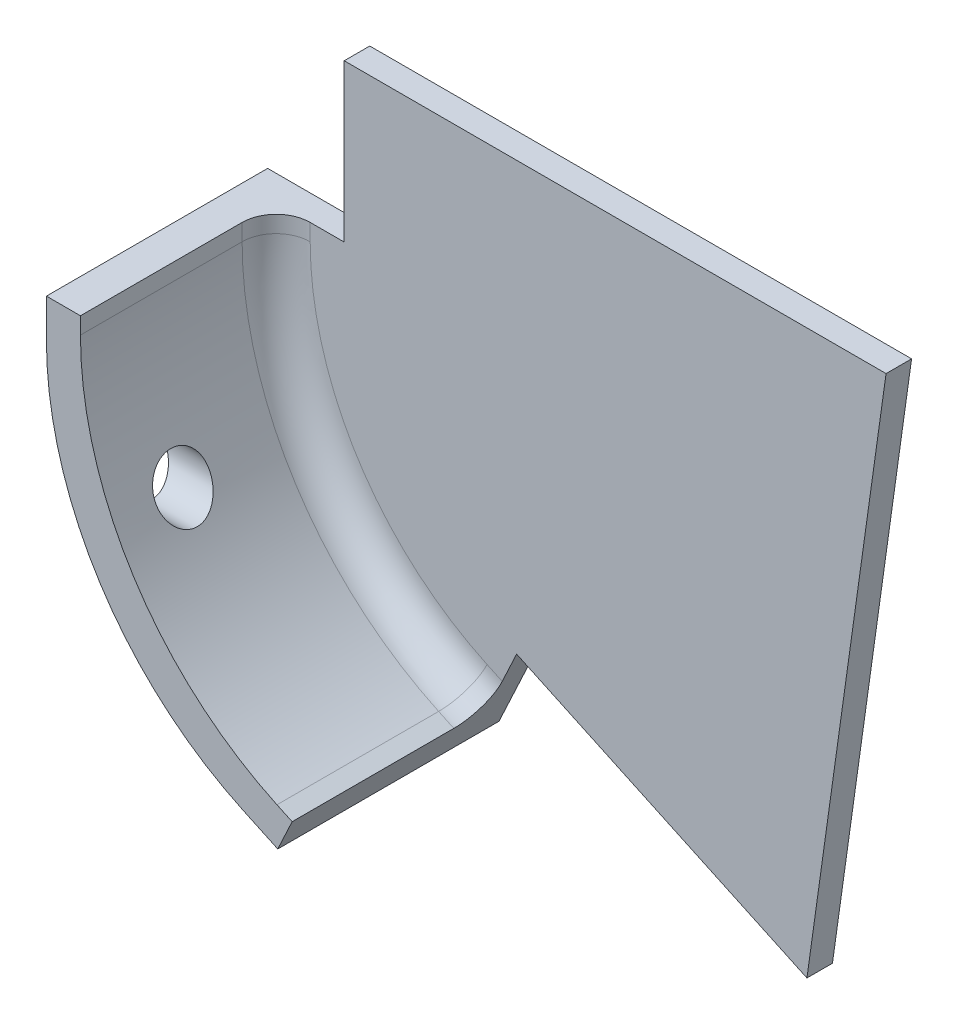
SolidWorks part; units mm, degrees
material "POLYURETHANE (11671)"
ref_plane "Front Plane" through (0, 0, 0) normal (0, 0, 1) x (1, 0, 0)
ref_plane "Top Plane" through (0, 0, 0) normal (0, 1, 0) x (1, 0, 0)
ref_plane "Right Plane" through (0, 0, 0) normal (1, 0, 0) x (0, 0, -1)
sketch "Sketch1" plane through (0, 0, 0) normal (0, 0, 1) x (1, 0, 0)
  line L0 (-4.4818, -31.0063) -> (9.1128, -37.3455)
  line L5 (-18.0764, -4.2621) -> (13.7624, -4.2621)
  line L6 (-18.0764, -4.2621) -> (-18.0764, -9.667)
  line L9 (9.1128, -37.3455) -> (13.7624, -4.2621)
  line L14 (-18.0764, -9.667) -> (-18.0764, -24.667)
  line L15 (-4.4818, -31.0063) -> (-18.0764, -24.667)
  dimension "D4" = 82
  dimension "D3" = 115
extrude "Boss-Extrude1" add sketch "Sketch1" along normal blind 1.5
sketch "Sketch2" plane through (0, 0, 0) normal (0, 0, -1) x (-1, 0, 0)
  line L0 (24.0764, -28.4894) -> (24.0764, -13.4894)
  line L1 (24.0764, -13.4894) -> (17.0764, -13.4894)
  line L2 (17.0764, -13.4894) -> (17.0764, -24.0299)
  line L5 (10.4818, -34.8287) -> (24.0764, -28.4894)
  line L6 (18.0764, -24.667) -> (-9.1128, -37.3455) construction
  line L7 (18.0764, -24.667) -> (-9.1128, -37.3455) construction
  line L8 (7.5235, -28.4845) -> (17.0764, -24.0299)
  line L9 (10.4818, -34.8287) -> (7.5235, -28.4845)
  line L13 (18.0764, -4.2621) -> (18.0764, -24.667) construction
  dimension "D1" = 7
  dimension "D2" = 7
  dimension "D3" = 15
  dimension "D4" = 15
  dimension "D5" = 1
  dimension "D6" = 1
extrude "Boss-Extrude2" add sketch "Sketch2" against normal blind 13
sketch "Sketch4" plane through (0, 0, 13) normal (0, 0, 1) x (1, 0, 0)
  line L0 (-17.0764, -13.4894) -> (-22.0764, -13.4894)
  line L1 (-22.0764, -13.4894) -> (-22.0764, -27.2153)
  line L2 (-22.0764, -27.2153) -> (-9.6365, -33.0161)
  line L3 (-9.6365, -33.0161) -> (-7.5235, -28.4845)
  line L4 (-7.5235, -28.4845) -> (-17.0764, -24.0299)
  line L5 (-17.0764, -24.0299) -> (-17.0764, -13.4894)
  line L6 (-24.0764, -13.4894) -> (-17.0764, -13.4894) construction
  line L7 (-7.5235, -28.4845) -> (-10.4818, -34.8287) construction
  line L8 (-17.0764, -24.0299) -> (-17.0764, -13.4894) construction
  line L9 (-17.0764, -24.0299) -> (-7.5235, -28.4845) construction
  dimension "D1" = 5
  dimension "D2" = 5
extrude "Cut-Extrude3" cut sketch "Sketch4" against normal blind 11.5
fillet "Fillet7" radius 20 2 edges at (-24.0764, -28.4894, 6.5) (-22.0764, -27.2153, 7.25)
fillet "Fillet8" radius 2 3 edges at (-22.0764, -13.9816, 1.5) (-10.0827, -32.808, 1.5) (-18.9442, -25.2199, 1.5)
sketch "Sketch5" plane through (-22.0764, 0, 0) normal (1, 0, 0) x (0, 0, -1)
  line L0 (-13, -13.4894) -> (-13, -14.4739) construction
  line L1 (-3.5, -13.4894) -> (-13, -13.4894) construction
  circle A0 centre (-9, -23.1894) radius 1.6
  dimension "D1" = 3.2
  dimension "D2" = 4
  dimension "D3" = 9.7
extrude "Cut-Extrude4" cut sketch "Sketch5" against normal mid plane 11.5
